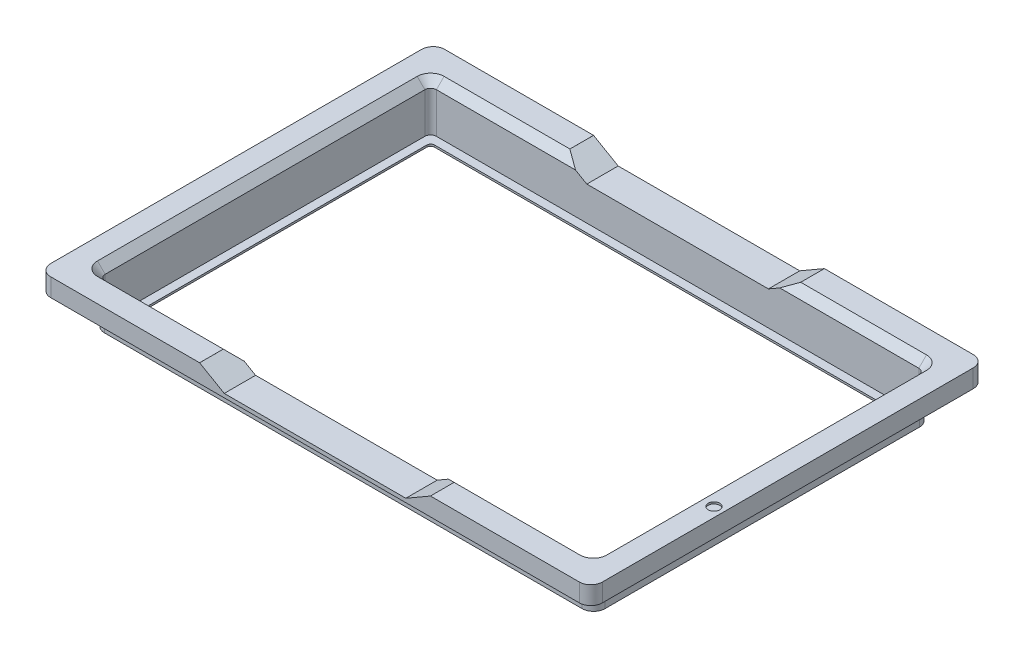
SolidWorks part; units mm, degrees
ref_plane "Front Plane" through (0, 0, 0) normal (0, 0, 1) x (1, 0, 0)
ref_plane "Top Plane" through (0, 0, 0) normal (0, 1, 0) x (1, 0, 0)
ref_plane "Right Plane" through (0, 0, 0) normal (1, 0, 0) x (0, 0, -1)
sketch "Sketch1" plane through (0, 0, 0) normal (0, 1, 0) x (1, 0, 0)
  line L1 (-71.7, 51.2) -> (71.7, 51.2)
  line L2 (-71.7, 51.2) -> (-71.7, -51.2)
  line L3 (-71.7, -51.2) -> (71.7, -51.2)
  line L4 (71.7, 51.2) -> (71.7, -51.2)
  line L5 (-71.7, 51.2) -> (71.7, -51.2) construction
  line L6 (-71.7, -51.2) -> (71.7, 51.2) construction
  line L7 (-62, 40.85) -> (62, 40.85)
  line L8 (-62, 40.85) -> (-62, -40.85)
  line L9 (-62, -40.85) -> (62, -40.85)
  line L10 (62, 40.85) -> (62, -40.85)
  line L11 (-62, 40.85) -> (62, -40.85) construction
  line L12 (-62, -40.85) -> (62, 40.85) construction
  point P0 (0, 0)
  point P6 (0, 0)
  dimension "D1" = 143.4
  dimension "D2" = 102.4
  dimension "D3" = 124
  dimension "D4" = 81.7
extrude "Boss-Extrude1" add sketch "Sketch1" along normal blind 13
sketch "Sketch2" plane through (0, 13, 0) normal (0, 1, 0) x (1, 0, 0)
  line L1 (-64.2, 43.05) -> (64.2, 43.05)
  line L2 (-64.2, 43.05) -> (-64.2, -43.05)
  line L3 (-64.2, -43.05) -> (64.2, -43.05)
  line L4 (64.2, 43.05) -> (64.2, -43.05)
  line L5 (-64.2, 43.05) -> (64.2, -43.05) construction
  line L6 (-64.2, -43.05) -> (64.2, 43.05) construction
  point P0 (0, 0)
  dimension "D1" = 128.4
  dimension "D2" = 86.1
extrude "Cut-Extrude1" cut sketch "Sketch2" against normal offset from surface (12.5 mm away) 0.5 up to face at (0, 0, 0)
sketch "Sketch3" plane through (0, 0, 0) normal (0, -1, 0) x (1, 0, 0)
  line L1 (-65.05, 43.85) -> (65.05, 43.85)
  line L2 (-65.05, 43.85) -> (-65.05, -43.85)
  line L3 (-65.05, -43.85) -> (65.05, -43.85)
  line L4 (65.05, 43.85) -> (65.05, -43.85)
  line L5 (-65.05, 43.85) -> (65.05, -43.85) construction
  line L6 (-65.05, -43.85) -> (65.05, 43.85) construction
  line L7 (-71.7, 51.2) -> (71.7, 51.2)
  line L8 (-71.7, 51.2) -> (-71.7, -51.2)
  line L9 (-71.7, -51.2) -> (71.7, -51.2)
  line L10 (71.7, 51.2) -> (71.7, -51.2)
  line L11 (-71.7, 51.2) -> (71.7, -51.2) construction
  line L12 (-71.7, -51.2) -> (71.7, 51.2) construction
  point P0 (0, 0)
  point P6 (0, 0)
  dimension "D1" = 87.7
  dimension "D2" = 130.1
extrude "Cut-Extrude3" cut sketch "Sketch3" against normal offset from surface (8.3 mm away) 4.7 up to face at (0, 13, 0)
fillet "Fillet1" radius 1 4 edges at (62, 0.25, 40.85) (-62, 0.25, 40.85) (62, 0.25, -40.85) (-62, 0.25, -40.85)
fillet "Fillet2" radius 1.5 4 edges at (-64.2, 6.75, 43.05) (64.2, 6.75, 43.05) (64.2, 6.75, -43.05) (-64.2, 6.75, -43.05)
fillet "Fillet3" radius 3 8 edges at (-65.05, 4.15, -43.85) (65.05, 4.15, -43.85) (65.05, 4.15, 43.85) (-65.05, 4.15, 43.85) (-71.7, 10.65, -51.2) (71.7, 10.65, -51.2) (71.7, 10.65, 51.2) (-71.7, 10.65, 51.2)
sketch "Sketch4" plane through (0, 13, 0) normal (0, 1, 0) x (1, 0, 0)
  line L0 (0, 51.2) -> (0, 43.05) construction
  line L1 (68.7, 51.2) -> (-68.7, 51.2) construction
  line L2 (62.7, 43.05) -> (-62.7, 43.05) construction
  line L3 (-62.7, 43.05) -> (62.7, 43.05) construction
  line L4 (-30, 51.2) -> (30, 51.2)
  line L5 (-30, 51.2) -> (-30, 43.05)
  line L6 (-30, 43.05) -> (30, 43.05)
  line L7 (30, 51.2) -> (30, 43.05)
  point P12 (0, 43.05)
  dimension "D1" = 60
extrude "Cut-Extrude4" cut sketch "Sketch4" against normal offset from surface (3.7 mm away) 1 up to face at (0, 8.3, 0)
mirror "Mirror1" about plane through (0, 0, 0) normal (0, 0, 1) of "Cut-Extrude4"
chamfer "Chamfer1" distance 6.4 angle 30 2 edges at (-30, 9.3, -47.125) (30, 9.3, -47.125)
chamfer "Chamfer2" distance 6.4 angle 30 2 edges at (30, 9.3, 47.125) (-30, 9.3, 47.125)
sketch "Sketch5" plane through (0, 13, 0) normal (0, 1, 0) x (1, 0, 0)
  line L0 (30, -51.2) -> (68.7, -51.2) construction
  line L1 (71.7, -48.2) -> (71.7, 48.2) construction
  circle A0 centre (69.2, -16.7) radius 1.5
  dimension "D3" = 3
  dimension "D1" = 34.5
  dimension "D2" = 2.5
extrude "Cut-Extrude5" cut sketch "Sketch5" against normal blind 0.5
chamfer "Chamfer3" distance 2 angle 45 10 edges at (46.35, 13, 43.05) (63.7607, 13, 42.6107) (64.2, 13, 0) (63.7607, 13, -42.6107) (46.35, 13, -43.05) (-46.35, 13, -43.05) (-46.35, 13, 43.05) (-63.7607, 13, -42.6107) (-63.7607, 13, 42.6107) (-64.2, 13, 0)
sketch "Sketch6" plane through (0, 8.3, 0) normal (0, -1, 0) x (1, 0, 0)
  line L1 (68, -47.5) -> (-68, -47.5) construction
  line L2 (68, -47.5) -> (68, 47.5) construction
  line L3 (68, 47.5) -> (-68, 47.5) construction
  line L4 (-68, -47.5) -> (-68, 47.5) construction
  line L5 (68, -47.5) -> (-68, 47.5) construction
  line L6 (68, 47.5) -> (-68, -47.5) construction
  point P0 (0, 0)
  dimension "D1" = 136
  dimension "D2" = 95
hole_wizard "Ø3.7 (3.7) Diameter Hole1" positions "Sketch7" profile "Sketch8" hole size "Ø3.7" standard "ANSI Metric"
sketch "Sketch7" plane through (0, 8.3, 0) normal (0, -1, 0) x (-1, 0, 0)
  point P0 (-68, 47.5)
  point P3 (-68, -47.5)
  point P6 (68, 47.5)
  point P9 (68, -47.5)
sketch "Sketch8" plane through (68, 8.3, -47.5) normal (1, 0, 0) x (0, 0, -1)
  line L0 (0, 0) -> (0, 4.1116)
  line L1 (0, 4.1116) -> (1.85, 3)
  line L2 (1.85, 3) -> (1.85, 0.025)
  line L3 (1.85, 0.025) -> (1.875, 0)
  line L5 (1.875, 0) -> (0, 0)
  line L6 (-1.85, 0.025) -> (-1.875, 0) construction
  line L10 (0, 4.1116) -> (-1.85, 3) construction
  line L11 (0, -6.35) -> (0, 107.95) construction
  dimension "Hole Dia." = 3.7
  dimension "Hole Depth" = 3
  dimension "Near C'Sink Dia." = 3.75
  dimension "Near C'Sink Angle" = 90
  dimension "Drill Angle" = 118
